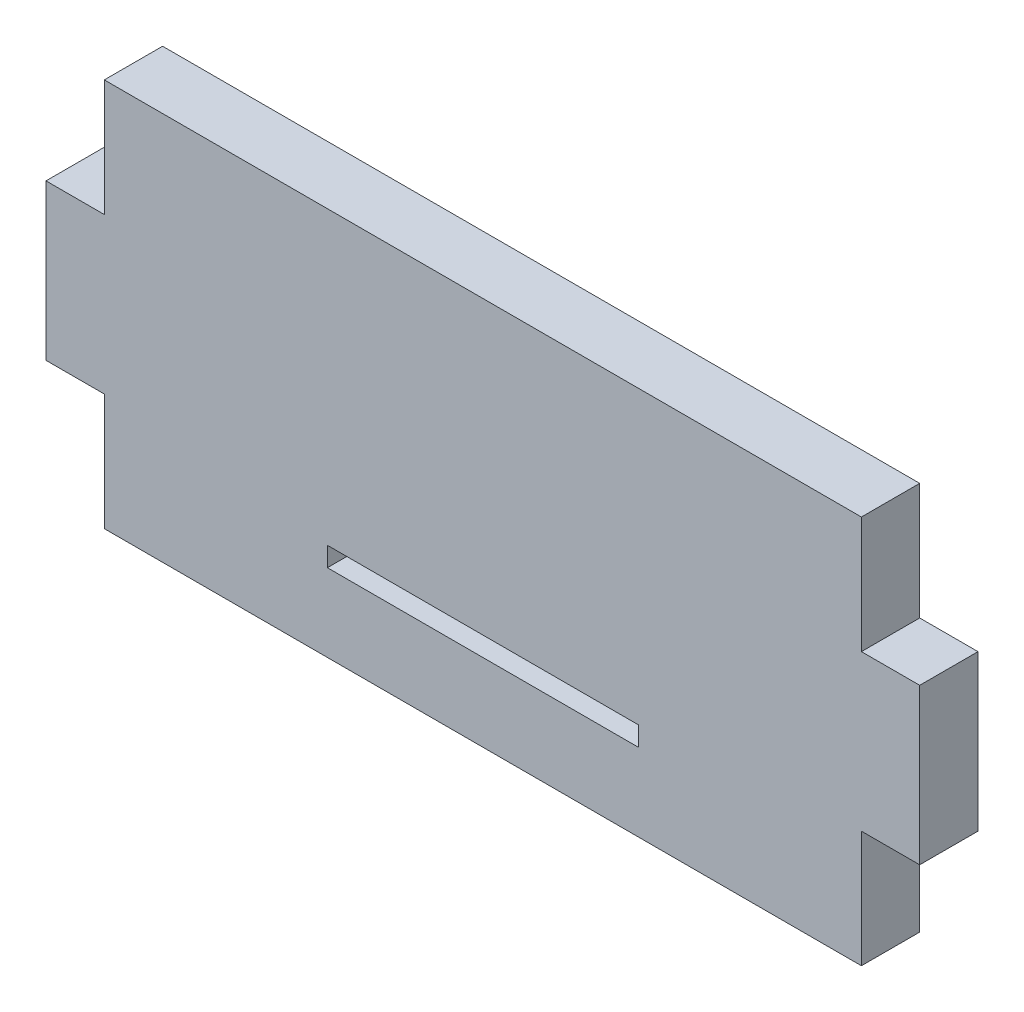
SolidWorks part; units mm, degrees
ref_plane "Front Plane" through (0, 0, 0) normal (0, 0, 1) x (1, 0, 0)
ref_plane "Top Plane" through (0, 0, 0) normal (0, 1, 0) x (1, 0, 0)
ref_plane "Right Plane" through (0, 0, 0) normal (1, 0, 0) x (0, 0, -1)
sketch "Sketch1" plane through (0, 0, 0) normal (0, 0, 1) x (1, 0, 0)
  line L0 (0, 44.45) -> (0, 63.5)
  line L1 (0, 0) -> (35.9685, 0)
  line L2 (0, 0) -> (0, 19.05)
  line L3 (0, 63.5) -> (123.698, 63.5)
  line L4 (123.698, 0) -> (123.698, 19.05)
  line L5 (0, 19.05) -> (-9.525, 19.05)
  line L7 (0, 44.45) -> (-9.525, 44.45)
  line L8 (-9.525, 19.05) -> (-9.525, 44.45)
  line L9 (61.849, 0) -> (61.849, 63.5) construction
  line L10 (123.698, 19.05) -> (133.223, 19.05)
  line L11 (133.223, 19.05) -> (133.223, 44.45)
  line L12 (123.698, 44.45) -> (133.223, 44.45)
  line L13 (123.698, 44.45) -> (123.698, 63.5)
  line L14 (35.9685, 0) -> (86.7685, 0)
  line L19 (86.7685, 0) -> (123.698, 0)
  line L21 (87.249, 12.7) -> (36.449, 12.7)
  line L22 (87.249, 12.7) -> (87.249, 15.875)
  line L23 (87.249, 15.875) -> (36.449, 15.875)
  line L24 (36.449, 12.7) -> (36.449, 15.875)
  dimension "D1" = 123.698
  dimension "D2" = 63.5
  dimension "D3" = 9.525
  dimension "D4" = 25.4
  dimension "D5" = 19.05
  dimension "D6" = 3.175
  dimension "D7" = 50.8
  dimension "D8" = 12.7
extrude "Boss-Extrude1" add sketch "Sketch1" along normal blind 9.525
